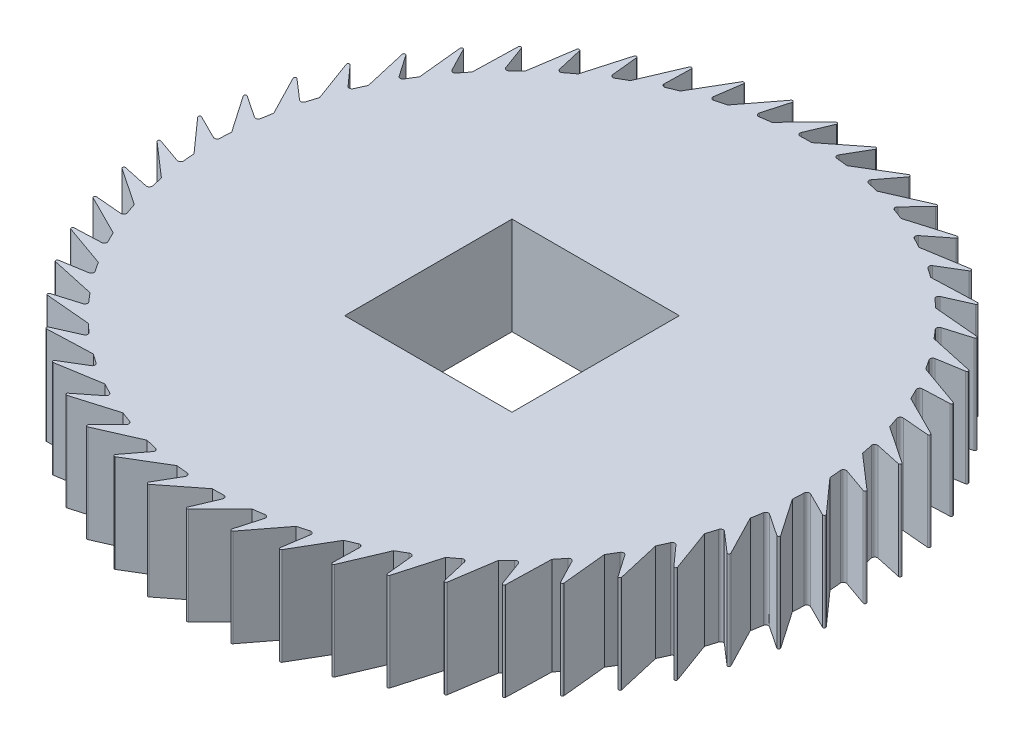
SolidWorks part; units mm, degrees
material "无缝钢管 45"
ref_plane "前视基准面" through (0, 0, 0) normal (0, 0, 1) x (1, 0, 0)
ref_plane "上视基准面" through (0, 0, 0) normal (0, 1, 0) x (1, 0, 0)
ref_plane "右视基准面" through (0, 0, 0) normal (1, 0, 0) x (0, 0, -1)
sketch "草图1" plane through (0, 0, 0) normal (0, 1, 0) x (1, 0, 0)
  line L0 (0, 30.8314) -> (0, -29.9629) construction
  line L1 (0, 21.5) -> (2.9528, 23.8177)
  line L2 (2.9528, 23.8177) -> (1.5733, 21.4424)
  line L3 (5.9147, 23.2598) -> (4.2483, 21.0761)
  line L4 (2.6947, 21.3305) -> (5.9147, 23.2598)
  line L5 (8.7833, 22.3351) -> (6.8564, 20.3774)
  line L6 (5.3468, 20.8245) -> (8.7833, 22.3351)
  line L7 (11.5133, 21.0581) -> (9.3563, 19.3574)
  line L8 (7.9147, 19.9902) -> (11.5133, 21.0581)
  line L9 (14.0618, 19.449) -> (11.7086, 18.0321)
  line L10 (10.3577, 18.8406) -> (14.0618, 19.449)
  line L11 (16.3885, 17.5333) -> (13.8763, 16.4225)
  line L12 (12.6374, 17.3939) -> (16.3885, 17.5333)
  line L13 (18.4568, 15.341) -> (15.8252, 14.5538)
  line L14 (14.7178, 15.6728) -> (18.4568, 15.341)
  line L15 (20.234, 12.9068) -> (17.5245, 12.4556)
  line L16 (16.566, 13.7046) -> (20.234, 12.9068)
  line L17 (21.6921, 10.269) -> (18.9474, 10.161)
  line L18 (18.1531, 11.5203) -> (21.6921, 10.269)
  line L19 (22.8081, 7.4693) -> (20.0715, 7.7061)
  line L20 (19.4538, 9.1543) -> (22.8081, 7.4693)
  line L21 (23.5644, 4.5518) -> (20.8791, 5.1298)
  line L22 (20.4477, 6.6439) -> (23.5644, 4.5518)
  line L23 (23.9491, 1.5625) -> (21.3574, 2.4725)
  line L24 (21.1192, 4.0287) -> (23.9491, 1.5625)
  line L25 (23.9561, -1.4515) -> (21.4988, -0.2238)
  line L26 (21.4576, 1.35) -> (23.9561, -1.4515)
  line L27 (23.5853, -4.4425) -> (21.3013, -2.9166)
  line L28 (21.4576, -1.35) -> (23.5853, -4.4425)
  line L29 (22.8425, -7.3635) -> (20.7677, -5.5633)
  line L30 (21.1192, -4.0287) -> (22.8425, -7.3635)
  line L31 (21.7395, -10.1684) -> (19.9067, -8.1224)
  line L32 (20.4477, -6.6439) -> (21.7395, -10.1684)
  line L33 (20.2936, -12.8128) -> (18.7317, -10.5533)
  line L34 (19.4538, -9.1543) -> (20.2936, -12.8128)
  line L35 (18.5277, -15.2553) -> (17.2614, -12.8178)
  line L36 (18.1531, -11.5203) -> (18.5277, -15.2553)
  line L37 (16.4696, -17.4571) -> (15.5188, -14.8801)
  line L38 (16.566, -13.7046) -> (16.4696, -17.4571)
  line L39 (14.1518, -19.3837) -> (13.5314, -16.7078)
  line L40 (14.7178, -15.6728) -> (14.1518, -19.3837)
  line L41 (11.6108, -21.0045) -> (11.3307, -18.272)
  line L42 (12.6374, -17.3939) -> (11.6108, -21.0045)
  line L43 (8.8867, -22.2941) -> (8.9512, -19.548)
  line L44 (10.3577, -18.8406) -> (8.8867, -22.2941)
  line L45 (6.0224, -23.2321) -> (6.4306, -20.5158)
  line L46 (7.9147, -19.9902) -> (6.0224, -23.2321)
  line L47 (3.0632, -23.8037) -> (3.8086, -21.16)
  line L48 (5.3468, -20.8245) -> (3.0632, -23.8037)
  line L49 (0.0556, -23.9999) -> (1.1265, -21.4705)
  line L50 (2.6947, -21.3305) -> (0.0556, -23.9999)
  line L51 (-2.9528, -23.8177) -> (-1.5733, -21.4424)
  line L52 (0, -21.5) -> (-2.9528, -23.8177)
  line L53 (-5.9147, -23.2598) -> (-4.2483, -21.0761)
  line L54 (-2.6947, -21.3305) -> (-5.9147, -23.2598)
  line L55 (-8.7833, -22.3351) -> (-6.8564, -20.3774)
  line L56 (-5.3468, -20.8245) -> (-8.7833, -22.3351)
  line L57 (-11.5133, -21.0581) -> (-9.3563, -19.3574)
  line L58 (-7.9147, -19.9902) -> (-11.5133, -21.0581)
  line L59 (-14.0618, -19.449) -> (-11.7086, -18.0321)
  line L60 (-10.3577, -18.8406) -> (-14.0618, -19.449)
  line L61 (-16.3885, -17.5333) -> (-13.8763, -16.4225)
  line L62 (-12.6374, -17.3939) -> (-16.3885, -17.5333)
  line L63 (-18.4568, -15.341) -> (-15.8252, -14.5538)
  line L64 (-14.7178, -15.6728) -> (-18.4568, -15.341)
  line L65 (-20.234, -12.9068) -> (-17.5245, -12.4556)
  line L66 (-16.566, -13.7046) -> (-20.234, -12.9068)
  line L67 (-21.6921, -10.269) -> (-18.9474, -10.161)
  line L68 (-18.1531, -11.5203) -> (-21.6921, -10.269)
  line L69 (-22.8081, -7.4693) -> (-20.0715, -7.7061)
  line L70 (-19.4538, -9.1543) -> (-22.8081, -7.4693)
  line L71 (-23.5644, -4.5518) -> (-20.8791, -5.1298)
  line L72 (-20.4477, -6.6439) -> (-23.5644, -4.5518)
  line L73 (-23.9491, -1.5625) -> (-21.3574, -2.4725)
  line L74 (-21.1192, -4.0287) -> (-23.9491, -1.5625)
  line L75 (-23.9561, 1.4515) -> (-21.4988, 0.2238)
  line L76 (-21.4576, -1.35) -> (-23.9561, 1.4515)
  line L77 (-23.5853, 4.4425) -> (-21.3013, 2.9166)
  line L78 (-21.4576, 1.35) -> (-23.5853, 4.4425)
  line L79 (-22.8425, 7.3635) -> (-20.7677, 5.5633)
  line L80 (-21.1192, 4.0287) -> (-22.8425, 7.3635)
  line L81 (-21.7395, 10.1684) -> (-19.9067, 8.1224)
  line L82 (-20.4477, 6.6439) -> (-21.7395, 10.1684)
  line L83 (-20.2936, 12.8128) -> (-18.7317, 10.5533)
  line L84 (-19.4538, 9.1543) -> (-20.2936, 12.8128)
  line L85 (-18.5277, 15.2553) -> (-17.2614, 12.8178)
  line L86 (-18.1531, 11.5203) -> (-18.5277, 15.2553)
  line L87 (-16.4696, 17.4571) -> (-15.5188, 14.8801)
  line L88 (-16.566, 13.7046) -> (-16.4696, 17.4571)
  line L89 (-14.1518, 19.3837) -> (-13.5314, 16.7078)
  line L90 (-14.7178, 15.6728) -> (-14.1518, 19.3837)
  line L91 (-11.6108, 21.0045) -> (-11.3307, 18.272)
  line L92 (-12.6374, 17.3939) -> (-11.6108, 21.0045)
  line L93 (-8.8867, 22.2941) -> (-8.9512, 19.548)
  line L94 (-10.3577, 18.8406) -> (-8.8867, 22.2941)
  line L95 (-6.0224, 23.2321) -> (-6.4306, 20.5158)
  line L96 (-7.9147, 19.9902) -> (-6.0224, 23.2321)
  line L97 (-3.0632, 23.8037) -> (-3.8086, 21.16)
  line L98 (-5.3468, 20.8245) -> (-3.0632, 23.8037)
  line L99 (-0.0556, 23.9999) -> (-1.1265, 21.4705)
  line L100 (-2.6947, 21.3305) -> (-0.0556, 23.9999)
  circle A0 centre (0, 0) radius 24 construction
  arc A1 (-14.7178, 15.6728) -> (-15.5188, 14.8801) centre (0, 0) ccw
  arc A2 (-12.6374, 17.3939) -> (-13.5314, 16.7078) centre (0, 0) ccw
  arc A3 (-10.3577, 18.8406) -> (-11.3307, 18.272) centre (0, 0) ccw
  arc A4 (-7.9147, 19.9902) -> (-8.9512, 19.548) centre (0, 0) ccw
  arc A5 (-5.3468, 20.8245) -> (-6.4306, 20.5158) centre (0, 0) ccw
  arc A6 (-2.6947, 21.3305) -> (-3.8086, 21.16) centre (0, 0) ccw
  arc A7 (0, 21.5) -> (-1.1265, 21.4705) centre (0, 0) ccw
  arc A8 (2.6947, 21.3305) -> (1.5733, 21.4424) centre (0, 0) ccw
  arc A9 (5.3468, 20.8245) -> (4.2483, 21.0761) centre (0, 0) ccw
  arc A10 (7.9147, 19.9902) -> (6.8564, 20.3774) centre (0, 0) ccw
  arc A11 (10.3577, 18.8406) -> (9.3563, 19.3574) centre (0, 0) ccw
  arc A12 (12.6374, 17.3939) -> (11.7086, 18.0321) centre (0, 0) ccw
  arc A13 (14.7178, 15.6728) -> (13.8763, 16.4225) centre (0, 0) ccw
  arc A14 (16.566, 13.7046) -> (15.8252, 14.5538) centre (0, 0) ccw
  arc A15 (18.1531, 11.5203) -> (17.5245, 12.4556) centre (0, 0) ccw
  arc A16 (19.4538, 9.1543) -> (18.9474, 10.161) centre (0, 0) ccw
  arc A17 (20.4477, 6.6439) -> (20.0715, 7.7061) centre (0, 0) ccw
  arc A18 (21.1192, 4.0287) -> (20.8791, 5.1298) centre (0, 0) ccw
  arc A19 (21.4576, 1.35) -> (21.3574, 2.4725) centre (0, 0) ccw
  arc A20 (21.4576, -1.35) -> (21.4988, -0.2238) centre (0, 0) ccw
  arc A21 (21.1192, -4.0287) -> (21.3013, -2.9166) centre (0, 0) ccw
  arc A22 (20.4477, -6.6439) -> (20.7677, -5.5633) centre (0, 0) ccw
  arc A23 (19.4538, -9.1543) -> (19.9067, -8.1224) centre (0, 0) ccw
  arc A24 (18.1531, -11.5203) -> (18.7317, -10.5533) centre (0, 0) ccw
  arc A25 (16.566, -13.7046) -> (17.2614, -12.8178) centre (0, 0) ccw
  arc A26 (14.7178, -15.6728) -> (15.5188, -14.8801) centre (0, 0) ccw
  arc A27 (12.6374, -17.3939) -> (13.5314, -16.7078) centre (0, 0) ccw
  arc A28 (10.3577, -18.8406) -> (11.3307, -18.272) centre (0, 0) ccw
  arc A29 (7.9147, -19.9902) -> (8.9512, -19.548) centre (0, 0) ccw
  arc A30 (5.3468, -20.8245) -> (6.4306, -20.5158) centre (0, 0) ccw
  arc A31 (2.6947, -21.3305) -> (3.8086, -21.16) centre (0, 0) ccw
  arc A32 (0, -21.5) -> (1.1265, -21.4705) centre (0, 0) ccw
  arc A33 (-2.6947, -21.3305) -> (-1.5733, -21.4424) centre (0, 0) ccw
  arc A34 (-5.3468, -20.8245) -> (-4.2483, -21.0761) centre (0, 0) ccw
  arc A35 (-7.9147, -19.9902) -> (-6.8564, -20.3774) centre (0, 0) ccw
  arc A36 (-10.3577, -18.8406) -> (-9.3563, -19.3574) centre (0, 0) ccw
  arc A37 (-12.6374, -17.3939) -> (-11.7086, -18.0321) centre (0, 0) ccw
  arc A38 (-14.7178, -15.6728) -> (-13.8763, -16.4225) centre (0, 0) ccw
  arc A39 (-16.566, -13.7046) -> (-15.8252, -14.5538) centre (0, 0) ccw
  arc A40 (-16.566, 13.7046) -> (-17.2614, 12.8178) centre (0, 0) ccw
  arc A41 (-18.1531, 11.5203) -> (-18.7317, 10.5533) centre (0, 0) ccw
  arc A42 (-19.4538, 9.1543) -> (-19.9067, 8.1224) centre (0, 0) ccw
  arc A43 (-20.4477, 6.6439) -> (-20.7677, 5.5633) centre (0, 0) ccw
  arc A44 (-21.1192, 4.0287) -> (-21.3013, 2.9166) centre (0, 0) ccw
  arc A45 (-21.4576, 1.35) -> (-21.4988, 0.2238) centre (0, 0) ccw
  arc A46 (-21.4576, -1.35) -> (-21.3574, -2.4725) centre (0, 0) ccw
  arc A47 (-21.1192, -4.0287) -> (-20.8791, -5.1298) centre (0, 0) ccw
  arc A48 (-20.4477, -6.6439) -> (-20.0715, -7.7061) centre (0, 0) ccw
  arc A49 (-19.4538, -9.1543) -> (-18.9474, -10.161) centre (0, 0) ccw
  arc A50 (-18.1531, -11.5203) -> (-17.5245, -12.4556) centre (0, 0) ccw
  point P159 (0, 0)
  dimension "D1" = 48
  dimension "D2" = 43
  dimension "D3" = 50
extrude "凸台-拉伸1" add sketch "草图1" along normal blind 7
fillet "圆角1" radius 0.2 14 edges at (-21.3013, 3.5, -2.9166) (-20.7677, 3.5, -5.5633) (-19.9067, 3.5, -8.1224) (-18.7317, 3.5, -10.5533) (-17.2614, 3.5, -12.8178) (-15.5188, 3.5, -14.8801) (-13.5314, 3.5, -16.7078) (-11.3307, 3.5, -18.272) (-8.9512, 3.5, -19.548) (-6.4306, 3.5, -20.5158) (-3.8086, 3.5, -21.16) (-1.1265, 3.5, -21.4705) (1.5733, 3.5, -21.4424) (4.2483, 3.5, -21.0761)
fillet "圆角2" radius 0.2 14 edges at (1.1265, 3.5, 21.4705) (-1.5733, 3.5, 21.4424) (-4.2483, 3.5, 21.0761) (-6.8564, 3.5, 20.3774) (-9.3563, 3.5, 19.3574) (-11.7086, 3.5, 18.0321) (-13.8763, 3.5, 16.4225) (-15.8252, 3.5, 14.5538) (-17.5245, 3.5, 12.4556) (-18.9474, 3.5, 10.161) (-20.0715, 3.5, 7.7061) (-20.8791, 3.5, 5.1298) (-21.3574, 3.5, 2.4725) (-21.4988, 3.5, -0.2238)
fillet "圆角3" radius 0.2 14 edges at (20.8791, 3.5, -5.1298) (21.3574, 3.5, -2.4725) (21.4988, 3.5, 0.2238) (21.3013, 3.5, 2.9166) (20.7677, 3.5, 5.5633) (19.9067, 3.5, 8.1224) (18.7317, 3.5, 10.5533) (17.2614, 3.5, 12.8178) (15.5188, 3.5, 14.8801) (13.5314, 3.5, 16.7078) (11.3307, 3.5, 18.272) (8.9512, 3.5, 19.548) (6.4306, 3.5, 20.5158) (3.8086, 3.5, 21.16)
fillet "圆角4" radius 0.2 8 edges at (6.8564, 3.5, -20.3774) (9.3563, 3.5, -19.3574) (11.7086, 3.5, -18.0321) (13.8763, 3.5, -16.4225) (15.8252, 3.5, -14.5538) (17.5245, 3.5, -12.4556) (18.9474, 3.5, -10.161) (20.0715, 3.5, -7.7061)
fillet "圆角6" radius 0.1 1 edges at (-18.4568, 3.5, 15.341)
fillet "圆角7" radius 0.1 20 edges at (23.9491, 3.5, -1.5625) (23.9561, 3.5, 1.4515) (23.5853, 3.5, 4.4425) (22.8425, 3.5, 7.3635) (21.7395, 3.5, 10.1684) (20.2936, 3.5, 12.8128) (18.5277, 3.5, 15.2553) (16.4696, 3.5, 17.4571) (14.1518, 3.5, 19.3837) (11.6108, 3.5, 21.0045) (8.8867, 3.5, 22.2941) (6.0224, 3.5, 23.2321) (3.0632, 3.5, 23.8037) (0.0556, 3.5, 23.9999) (-2.9528, 3.5, 23.8177) (-5.9147, 3.5, 23.2598) (-8.7833, 3.5, 22.3351) (-11.5133, 3.5, 21.0581) (-14.0618, 3.5, 19.449) (-16.3885, 3.5, 17.5333)
fillet "圆角8" radius 0.1 20 edges at (-20.2936, 3.5, -12.8128) (-18.5277, 3.5, -15.2553) (-16.4696, 3.5, -17.4571) (-14.1518, 3.5, -19.3837) (-11.6108, 3.5, -21.0045) (-8.8867, 3.5, -22.2941) (-6.0224, 3.5, -23.2321) (-3.0632, 3.5, -23.8037) (-0.0556, 3.5, -23.9999) (2.9528, 3.5, -23.8177) (5.9147, 3.5, -23.2598) (8.7833, 3.5, -22.3351) (11.5133, 3.5, -21.0581) (14.0618, 3.5, -19.449) (16.3885, 3.5, -17.5333) (18.4568, 3.5, -15.341) (20.234, 3.5, -12.9068) (21.6921, 3.5, -10.269) (22.8081, 3.5, -7.4693) (23.5644, 3.5, -4.5518)
fillet "圆角9" radius 0.1 9 edges at (-20.234, 3.5, 12.9068) (-21.6921, 3.5, 10.269) (-22.8081, 3.5, 7.4693) (-23.5644, 3.5, 4.5518) (-23.9491, 3.5, 1.5625) (-23.9561, 3.5, -1.4515) (-23.5853, 3.5, -4.4425) (-22.8425, 3.5, -7.3635) (-21.7395, 3.5, -10.1684)
sketch "草图2" plane through (0, 7, 0) normal (0, 1, 0) x (1, 0, 0)
  line L1 (-6, 6) -> (6, 6)
  line L2 (-6, 6) -> (-6, -6)
  line L3 (-6, -6) -> (6, -6)
  line L4 (6, 6) -> (6, -6)
  line L5 (-6, 6) -> (6, -6) construction
  line L6 (-6, -6) -> (6, 6) construction
  point P0 (0, 0)
  dimension "D1" = 12
  dimension "D2" = 12
extrude "切除-拉伸1" cut sketch "草图2" against normal blind 7
